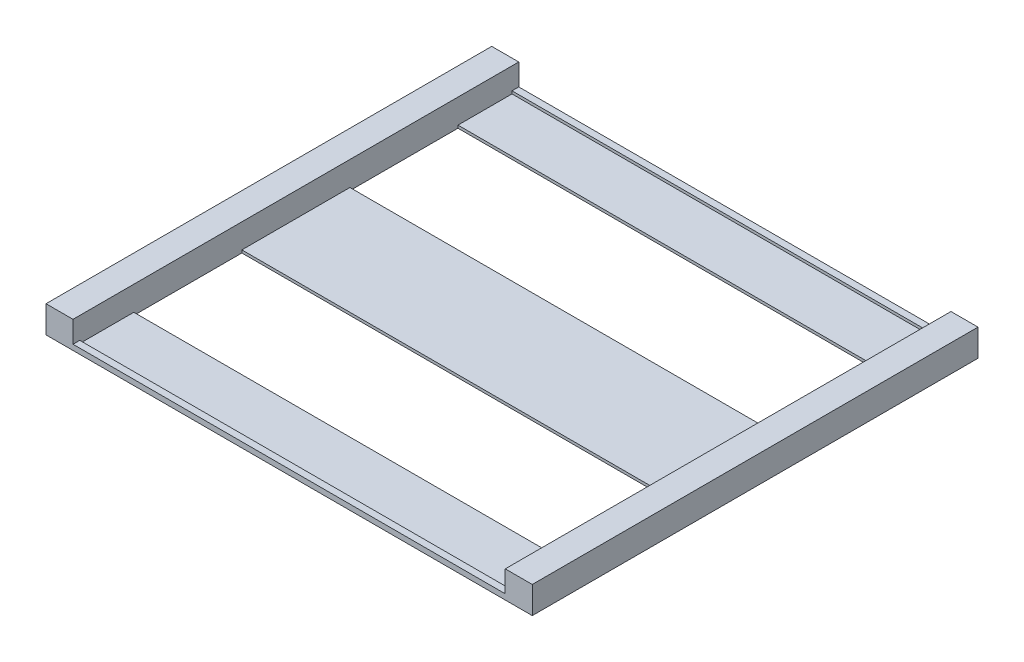
SolidWorks part; units mm, degrees
ref_plane "Front Plane" through (0, 0, 0) normal (0, 0, 1) x (1, 0, 0)
ref_plane "Top Plane" through (0, 0, 0) normal (0, 1, 0) x (1, 0, 0)
ref_plane "Right Plane" through (0, 0, 0) normal (1, 0, 0) x (0, 0, -1)
sketch "Sketch5" plane through (0, 0, 0) normal (0, 1, 0) x (1, 0, 0)
  line L1 (-90, 82.5) -> (90, 82.5)
  line L2 (-90, 82.5) -> (-90, -82.5)
  line L3 (-90, -82.5) -> (90, -82.5)
  line L4 (90, 82.5) -> (90, -82.5)
  line L5 (-90, 82.5) -> (-80, 82.5)
  line L6 (-90, 82.5) -> (-90, -82.5)
  line L7 (-90, -82.5) -> (-80, -82.5)
  line L8 (-80, 82.5) -> (-80, -82.5)
  line L9 (90, 82.5) -> (80, 82.5)
  line L10 (90, 82.5) -> (90, -82.5)
  line L11 (90, -82.5) -> (80, -82.5)
  line L12 (80, 82.5) -> (80, -82.5)
  line L13 (-80, 82.5) -> (80, 82.5)
  line L14 (-80, 82.5) -> (-80, 60)
  line L15 (-80, 60) -> (80, 60)
  line L16 (80, 82.5) -> (80, 60)
  line L17 (-80, -82.5) -> (80, -82.5)
  line L18 (-80, -82.5) -> (-80, -60)
  line L19 (-80, -60) -> (80, -60)
  line L20 (80, -82.5) -> (80, -60)
  line L21 (-80, 20) -> (80, 20)
  line L22 (-80, 20) -> (-80, -20)
  line L23 (-80, -20) -> (80, -20)
  line L24 (80, 20) -> (80, -20)
extrude "Boss-Extrude3" add sketch "Sketch5" along normal blind 1 contours L6 L5 L8 L7 | L22 L21 L24 L23 | L14 L13 L16 L15 | L18 L17 L20 L19 | L10 L9 L12 L11
sketch "Sketch6" plane through (0, 1, 0) normal (0, 1, 0) x (1, 0, 0)
  line L0 (-90, -82.5) -> (90, -82.5) construction
  line L1 (-90, 82.5) -> (-80, 82.5)
  line L2 (-90, 82.5) -> (-90, -82.5)
  line L3 (-90, -82.5) -> (-80, -82.5)
  line L4 (-80, 82.5) -> (-80, -82.5)
  line L6 (90, 82.5) -> (80, 82.5)
  line L7 (90, 82.5) -> (90, -82.5)
  line L8 (90, -82.5) -> (80, -82.5)
  line L9 (80, 82.5) -> (80, -82.5)
extrude "Boss-Extrude4" add sketch "Sketch6" along normal blind 9
sketch "Sketch7" plane through (0, 1, 0) normal (0, 1, 0) x (1, 0, 0)
  line L0 (80, 82.5) -> (80, -82.5) construction
  line L1 (-80, -82.5) -> (80, -82.5)
  line L2 (-80, -82.5) -> (-80, -80)
  line L3 (-80, -80) -> (80, -80)
  line L4 (80, -82.5) -> (80, -80)
extrude "Boss-Extrude5" add sketch "Sketch7" along normal blind 1
sketch "Sketch10" plane through (0, 1, 0) normal (0, 1, 0) x (1, 0, 0)
  line L0 (80, 82.5) -> (80, 60) construction
  line L1 (-80, 82.5) -> (80, 82.5)
  line L2 (-80, 82.5) -> (-80, 80)
  line L3 (-80, 80) -> (80, 80)
  line L4 (80, 82.5) -> (80, 80)
extrude "Boss-Extrude6" add sketch "Sketch10" along normal blind 1
